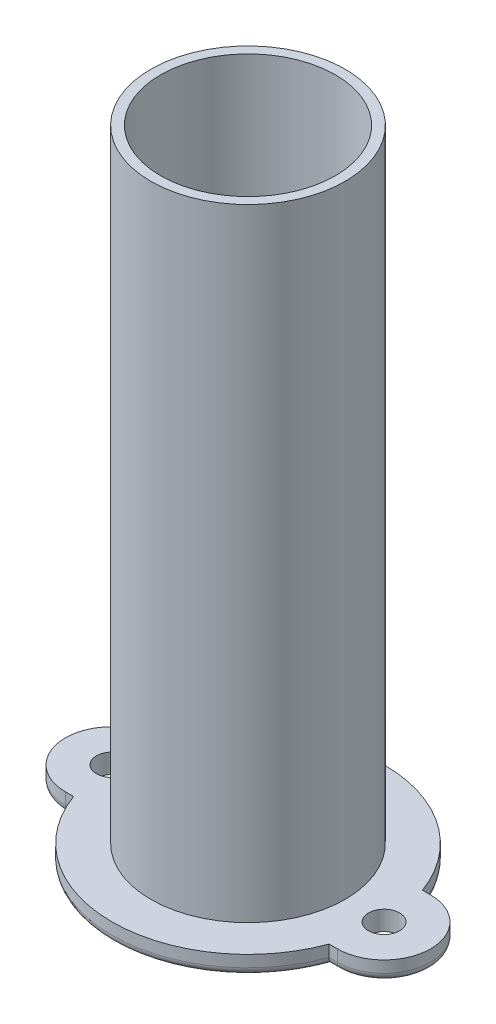
SolidWorks part; units mm, degrees
ref_plane "Alzado" through (0, 0, 0) normal (0, 0, 1) x (1, 0, 0)
ref_plane "Planta" through (0, 0, 0) normal (0, 1, 0) x (1, 0, 0)
ref_plane "Vista lateral" through (0, 0, 0) normal (1, 0, 0) x (0, 0, -1)
sketch "Croquis1" plane through (0, 0, 0) normal (0, 1, 0) x (1, 0, 0)
  line L0 (-17.5, 0) -> (17.5, 0) construction
  line L1 (-17.5, -6) -> (-17.5, 6) construction
  line L2 (-17.5, 6) -> (-16.4393, 6)
  line L3 (-17.5, -6) -> (-16.4393, -6)
  line L4 (0, 17.5) -> (0, -17.5) construction
  line L5 (17.5, 6) -> (16.4393, 6)
  line L6 (17.5, -6) -> (16.4393, -6)
  arc A0 (16.4393, 6) -> (-16.4393, 6) centre (0, 0) ccw
  circle A2 centre (0, 0) radius 11.25
  arc A5 (-17.5, 6) -> (-17.5, -6) centre (-17.5, 0) ccw
  arc A7 (17.5, 6) -> (17.5, -6) centre (17.5, 0) cw
  arc A8 (-16.4393, -6) -> (16.4393, -6) centre (0, 0) ccw
  circle A9 centre (-17.5, 0) radius 2
  circle A10 centre (17.5, 0) radius 2
  point P9 (-17.5, 0)
  dimension "D1" = 35
  dimension "D2" = 22.5
  dimension "D3" = 6
  dimension "D4" = 4
  dimension "D5" = 4
extrude "Saliente-Extruir2" add sketch "Croquis1" along normal blind 2.5
sketch "Croquis2" plane through (0, 2.5, 0) normal (0, 1, 0) x (1, 0, 0)
  circle A0 centre (0, 0) radius 12.5
  circle A1 centre (0, 0) radius 11.25
  circle M10 centre (0, 0) radius 11.25
  dimension "D1" = 25
  dimension "D2" = 22.5
extrude "Saliente-Extruir4" add sketch "Croquis2" along normal blind 80 contours A0 M10
fillet "Redondeo1" radius 1 9 edges at (0, 0, 11.25) (-16.9696, 0, 6) (0, 0, 17.5) (16.9696, 0, 6) (23.5, 0, 0) (16.9696, 0, -6) (0, 0, -17.5) (-16.9696, 0, -6) (-23.5, 0, 0)
